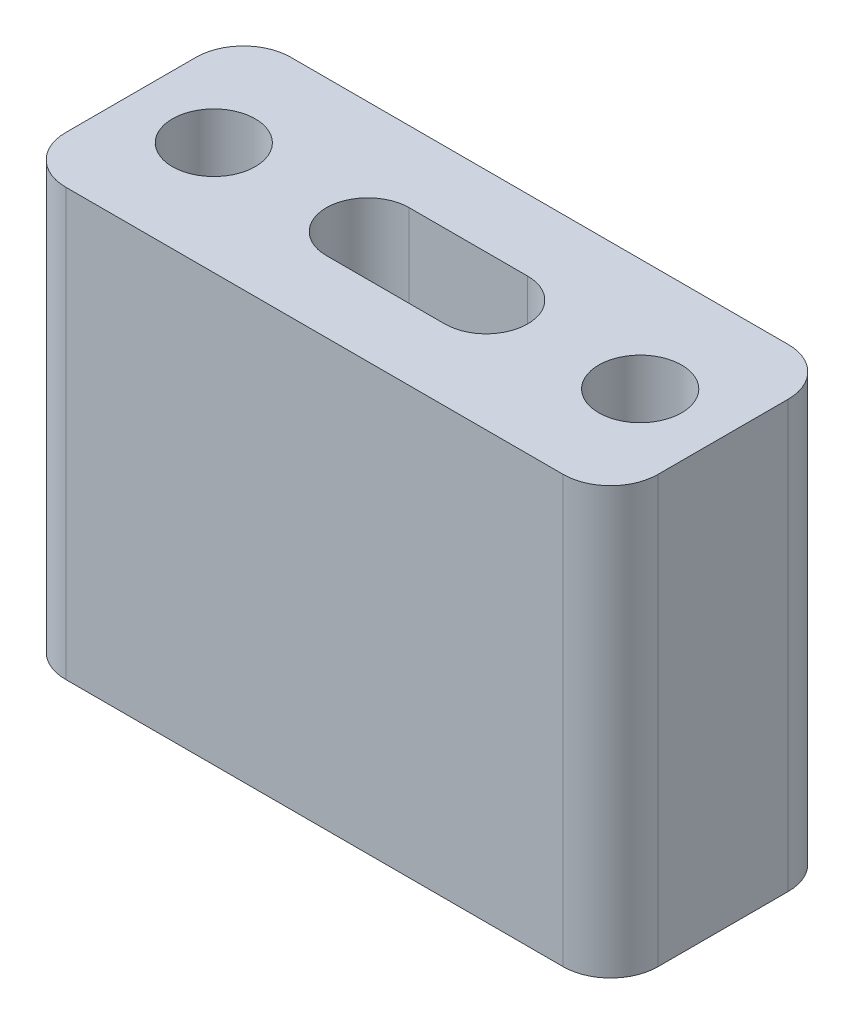
SolidWorks part; units mm, degrees
ref_plane "前视基准面" through (0, 0, 0) normal (0, 0, 1) x (1, 0, 0)
ref_plane "上视基准面" through (0, 0, 0) normal (0, 1, 0) x (1, 0, 0)
ref_plane "右视基准面" through (0, 0, 0) normal (1, 0, 0) x (0, 0, -1)
other "Configuration Table"
sketch "草图1" plane through (0, 0, 0) normal (0, 1, 0) x (1, 0, 0)
  line L0 (-9, 0) -> (9, 0) construction
  line L1 (-12.5, 4.75) -> (12.5, 4.75)
  line L2 (-12.5, 4.75) -> (-12.5, -4.75)
  line L3 (-12.5, -4.75) -> (12.5, -4.75)
  line L4 (12.5, 4.75) -> (12.5, -4.75)
  line L5 (-12.5, 4.75) -> (12.5, -4.75) construction
  line L6 (-12.5, -4.75) -> (12.5, 4.75) construction
  line L7 (-2.5, 0) -> (2.5, 0) construction
  line L8 (-2.5, 1.75) -> (2.5, 1.75)
  line L9 (-2.5, -1.75) -> (2.5, -1.75)
  circle A0 centre (-9, 0) radius 1.75
  circle A1 centre (9, 0) radius 1.75
  arc A2 (-2.5, 1.75) -> (-2.5, -1.75) centre (-2.5, 0) ccw
  arc A3 (2.5, -1.75) -> (2.5, 1.75) centre (2.5, 0) ccw
  point P0 (0, 0)
  point P10 (0, 0)
  point P13 (0, 0)
  dimension "D1" = 3.5
  dimension "D2" = 18
  dimension "D3" = 9.5
  dimension "D4" = 25
  dimension "D5" = 5
extrude "凸台-拉伸1" add sketch "草图1" along normal blind 18
fillet "圆角1" radius 2 4 edges at (-12.5, 9, 4.75) (-12.5, 9, -4.75) (12.5, 9, -4.75) (12.5, 9, 4.75)
